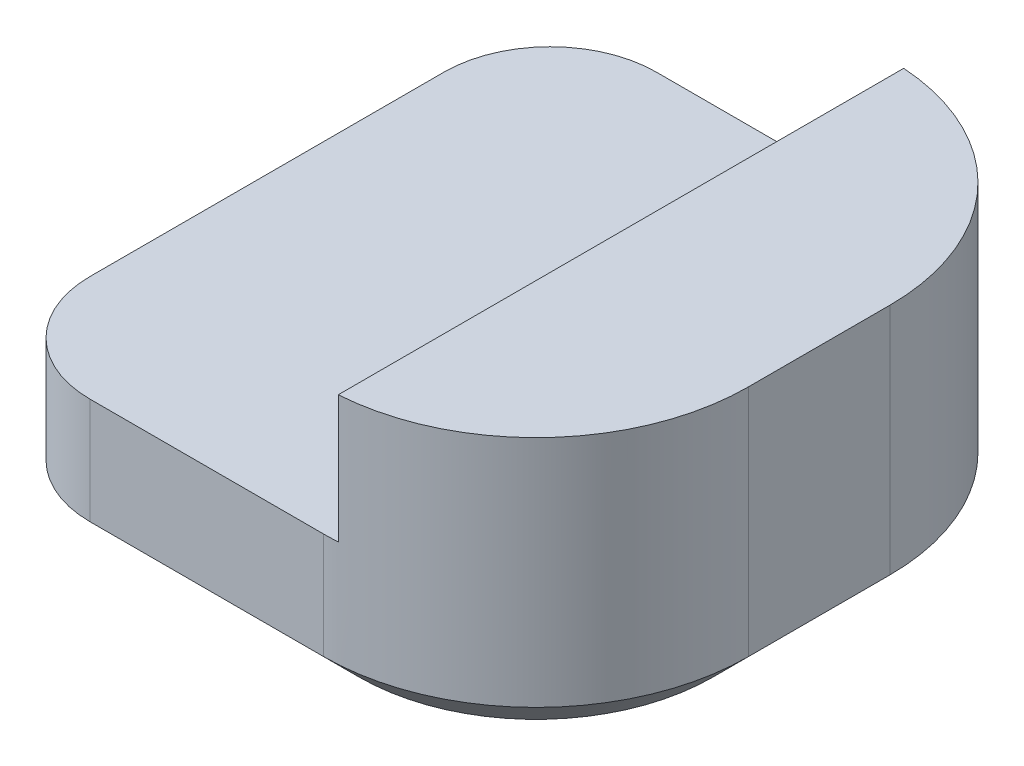
SolidWorks part; units mm, degrees
ref_plane "Front Plane" through (0, 0, 0) normal (0, 0, 1) x (1, 0, 0)
ref_plane "Top Plane" through (0, 0, 0) normal (0, 1, 0) x (1, 0, 0)
ref_plane "Right Plane" through (0, 0, 0) normal (1, 0, 0) x (0, 0, -1)
sketch "Sketch1" plane through (0, 0, 0) normal (0, 0, 1) x (1, 0, 0)
  line L0 (0, 0) -> (5, 0)
  line L1 (5, 0) -> (5, 1.8)
  line L2 (5, 1.8) -> (7.8, 1.8)
  line L3 (7.8, 1.8) -> (7.8, 0)
  line L6 (6.4304, -2) -> (0, -2)
  line L7 (0, -2) -> (0, 0)
  line L8 (6.4304, -2) -> (7.8, -2)
  line L9 (7.8, -2) -> (7.8, -0.3291)
  line L10 (7.8, 0) -> (7.8, -0.3291)
  dimension "D1" = 2
  dimension "D2" = 1.8
  dimension "D3" = 2.8
  dimension "D4" = 5
extrude "Boss-Extrude1" add sketch "Sketch1" along normal blind 8
fillet "Fillet1" radius 3 2 edges at (7.8, -0.1, 0) (7.8, -0.1, 8)
fillet "Fillet2" radius 1.5 2 edges at (0, -1, 0) (0, -1, 8)
chamfer "Chamfer1" distance 0.5 angle 45 8 edges at (3.15, -2, 8) (0.4393, -2, 7.5607) (6.9213, -2, 7.1213) (0, -2, 4) (7.8, -2, 4) (0.4393, -2, 0.4393) (6.9213, -2, 0.8787) (3.15, -2, 0)
